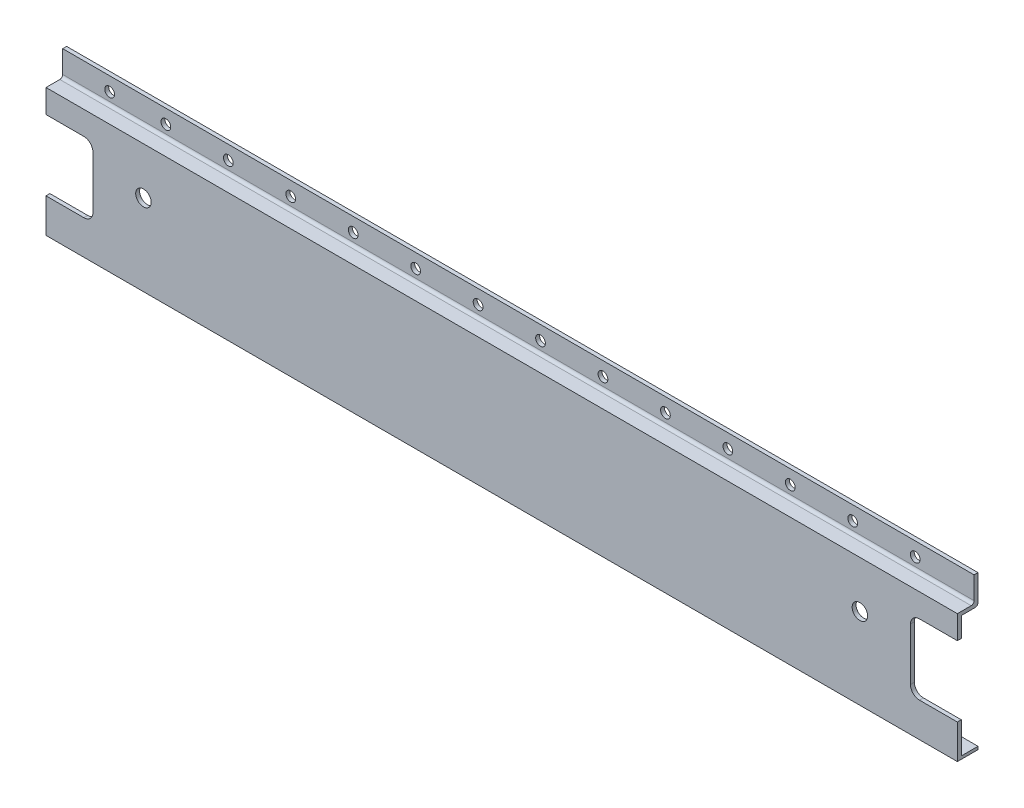
SolidWorks part; units mm, degrees
ref_plane "Front Plane" through (0, 0, 0) normal (0, 0, 1) x (1, 0, 0)
ref_plane "Top Plane" through (0, 0, 0) normal (0, 1, 0) x (1, 0, 0)
ref_plane "Right Plane" through (0, 0, 0) normal (1, 0, 0) x (0, 0, -1)
sketch "Sketch1" plane through (0, 0, 0) normal (0, 0, 1) x (1, 0, 0)
  line L1 (-320.675, -53.975) -> (320.675, -53.975)
  line L2 (-320.675, -53.975) -> (-320.675, 53.975)
  line L3 (-320.675, 53.975) -> (320.675, 53.975)
  line L4 (320.675, -53.975) -> (320.675, 53.975)
  line L5 (-320.675, -53.975) -> (320.675, 53.975) construction
  line L6 (-320.675, 53.975) -> (320.675, -53.975) construction
  point P0 (0, 0)
  dimension "D1" = 107.95
  dimension "D2" = 641.35
extrude "Boss-Extrude1" add sketch "Sketch1" along normal blind 14.5161
sketch "Sketch2" plane through (0, 0, 14.5161) normal (0, 0, 1) x (1, 0, 0)
  line L0 (320.675, -53.975) -> (320.675, 53.975) construction
  line L1 (-320.675, 53.975) -> (320.675, 53.975)
  line L2 (-320.675, 53.975) -> (-320.675, 36.195)
  line L3 (-320.675, 36.195) -> (320.675, 36.195)
  line L4 (320.675, 53.975) -> (320.675, 36.195)
  dimension "D1" = 17.78
extrude "Cut-Extrude1" cut sketch "Sketch2" against normal blind 11.7602
sketch "Sketch3" plane through (0, 0, 0) normal (0, 0, -1) x (-1, 0, 0)
  line L0 (-320.675, 53.975) -> (-320.675, 33.655)
  line L1 (-320.675, -53.975) -> (-320.675, 53.975) construction
  line L2 (320.675, 53.975) -> (320.675, -53.975) construction
  line L3 (-320.675, 33.655) -> (320.675, 33.655)
  line L4 (-320.675, 33.655) -> (-320.675, -51.8795)
  line L5 (-320.675, -51.8795) -> (320.675, -51.8795)
  line L6 (320.675, 33.655) -> (320.675, -51.8795)
  line L7 (320.675, -53.975) -> (-320.675, -53.975) construction
  line M3 (-320.675, 53.975) -> (-320.675, -53.975)
  line M5 (320.675, -53.975) -> (320.675, 53.975)
  dimension "D1" = 20.32
  dimension "D2" = 2.0955
extrude "Cut-Extrude3" cut sketch "Sketch3" against normal blind 11.7602 contours L5 L3 M3 M5
fillet "Fillet1" radius 2.032 2 edges at (0, 36.195, 2.7559) (0, 33.655, 0)
sketch "Sketch4" plane through (0, 0, 11.7602) normal (0, 0, -1) x (-1, 0, 0)
  line L0 (0, -51.8795) -> (0, -13.5829)
  line L1 (-320.675, 33.655) -> (-320.675, -51.8795) construction
  line L2 (-320.675, 19.685) -> (-294.005, 19.685)
  line L3 (-287.655, 13.335) -> (-287.655, -23.495)
  line L4 (-294.005, -29.845) -> (-320.675, -29.845)
  line L5 (-320.675, -29.845) -> (-320.675, 19.685)
  line L6 (-320.675, -51.8795) -> (320.675, -51.8795) construction
  line L7 (320.675, -29.845) -> (320.675, 19.685)
  line L8 (294.005, -29.845) -> (320.675, -29.845)
  line L9 (287.655, 13.335) -> (287.655, -23.495)
  line L10 (320.675, 19.685) -> (294.005, 19.685)
  arc A0 (-294.005, -29.845) -> (-287.655, -23.495) centre (-294.005, -23.495) ccw
  arc A1 (-287.655, 13.335) -> (-294.005, 19.685) centre (-294.005, 13.335) ccw
  arc A2 (287.655, 13.335) -> (294.005, 19.685) centre (294.005, 13.335) cw
  arc A3 (294.005, -29.845) -> (287.655, -23.495) centre (294.005, -23.495) cw
  point P11 (-287.655, 19.685)
  point P25 (287.655, 19.685)
  line M9 (-320.675, 33.655) -> (-320.675, -51.8795)
  line M11 (320.675, -51.8795) -> (320.675, 33.655)
  dimension "D3" = 6.35
  dimension "D1" = 33.02
  dimension "D2" = 49.53
extrude "Cut-Extrude4" cut sketch "Sketch4" against normal through all contours L3 A1 L2 L4 A0 M9 | A3 L8 L10 A2 L9 M11
sketch "Sketch5" plane through (0, 0, 0) normal (0, 0, -1) x (-1, 0, 0)
  line L0 (320.675, 53.975) -> (320.675, 38.227) construction
  circle A0 centre (-279.2221, 44.1482) radius 3.429
  circle A1 centre (-235.2801, 44.1482) radius 3.429
  circle A2 centre (-191.3381, 44.1482) radius 3.429
  circle A3 centre (-147.3961, 44.1482) radius 3.429
  circle A4 centre (-103.4541, 44.1482) radius 3.429
  circle A5 centre (-59.5121, 44.1482) radius 3.429
  circle A6 centre (-15.5701, 44.1482) radius 3.429
  circle A7 centre (28.3719, 44.1482) radius 3.429
  circle A8 centre (72.3139, 44.1482) radius 3.429
  circle A9 centre (116.2559, 44.1482) radius 3.429
  circle A10 centre (160.1979, 44.1482) radius 3.429
  circle A11 centre (204.1399, 44.1482) radius 3.429
  circle A12 centre (248.0819, 44.1482) radius 3.429
  circle A13 centre (287.655, 44.1482) radius 3.429
  point P30 (0, 0)
  point P31 (0, 0)
  dimension "D1" = 6.858
  dimension "D2" = 33.02
extrude "Cut-Extrude5" cut sketch "Sketch5" against normal blind 11.7602 contours A0 | A1 | A2 | A3 | A4 | A6 | A5 | A7 | A8 | A9 | A10 | A13 | A12 | A11
sketch "Sketch6" plane through (0, 0, 11.7602) normal (0, 0, -1) x (-1, 0, 0)
  line L0 (-287.655, -5.08) -> (-252.095, -5.08)
  line L1 (-287.655, 13.335) -> (-287.655, -23.495) construction
  line L2 (-252.095, 53.975) -> (-252.095, 3.175)
  line L3 (-320.675, 53.975) -> (320.675, 53.975) construction
  line L4 (0, 0) -> (0, 74.9965)
  circle A0 centre (-252.095, 3.175) radius 5.461
  circle A1 centre (252.095, 3.175) radius 5.461
  dimension "D3" = 10.922
  dimension "D1" = 35.56
  dimension "D2" = 50.8
extrude "Cut-Extrude6" cut sketch "Sketch6" against normal blind 11.7602
